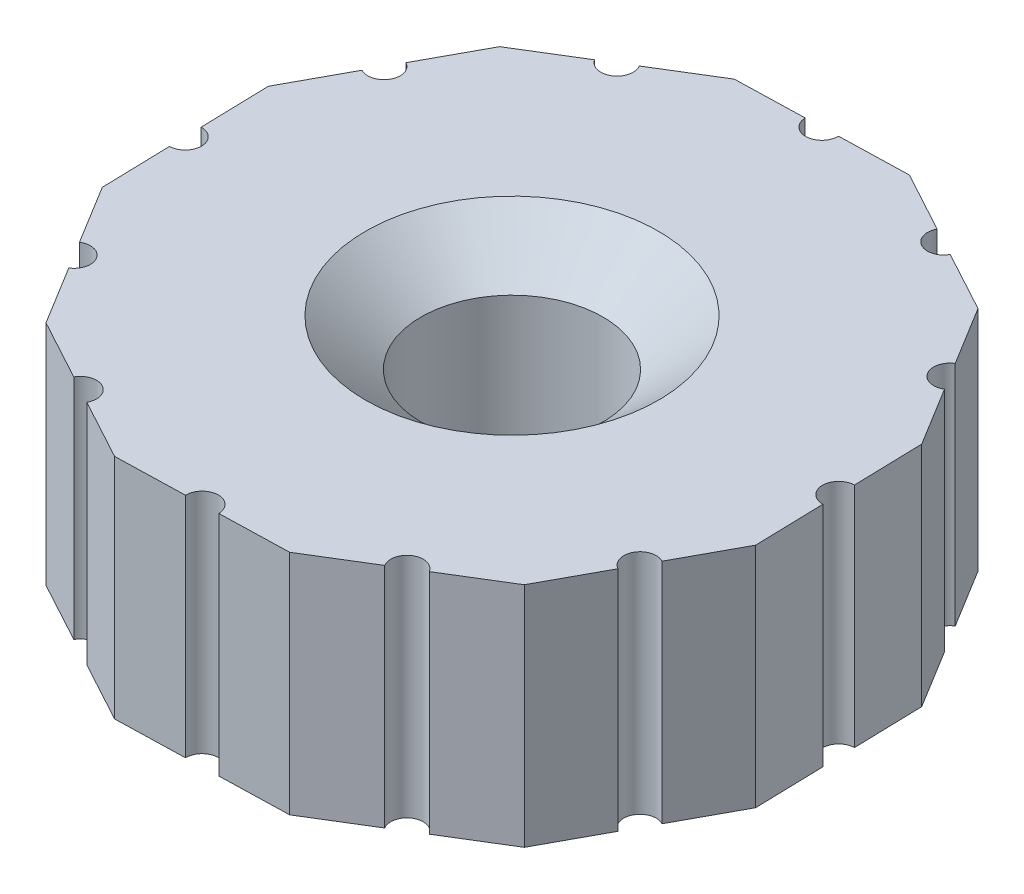
SolidWorks part; units mm, degrees
ref_plane "Front Plane" through (0, 0, 0) normal (0, 0, 1) x (1, 0, 0)
ref_plane "Top Plane" through (0, 0, 0) normal (0, 1, 0) x (1, 0, 0)
ref_plane "Right Plane" through (0, 0, 0) normal (1, 0, 0) x (0, 0, -1)
sketch "Sketch1" plane through (0, 0, 0) normal (0, 1, 0) x (1, 0, 0)
  line L0 (-63.9099, 8.5734) -> (-63.7113, 1.0734)
  line L1 (-35.7211, 1.8147) -> (-35.9197, 9.3146)
  line L2 (-35.9197, 9.3146) -> (-39.8417, 15.7105)
  line L3 (-39.8417, 15.7105) -> (-46.4361, 19.2884)
  line L4 (-46.4361, 19.2884) -> (-53.9361, 19.0898)
  line L5 (-53.9361, 19.0898) -> (-60.3319, 15.1678)
  line L6 (-60.3319, 15.1678) -> (-63.9099, 8.5734)
  line L7 (-63.7113, 1.0734) -> (-59.7893, -5.3224)
  line L8 (-59.7893, -5.3224) -> (-53.1948, -8.9004)
  line L9 (-53.1948, -8.9004) -> (-45.6949, -8.7018)
  line L10 (-45.6949, -8.7018) -> (-39.299, -4.7798)
  line L11 (-39.299, -4.7798) -> (-35.7211, 1.8147)
  circle A1 centre (-49.8155, 5.194) radius 14 construction
  arc A2 (-56.5263, 17.5015) -> (-57.7417, 16.7562) centre (-57.134, 17.1288) cw
  arc A3 (-49.4735, 19.208) -> (-50.8987, 19.1703) centre (-50.1861, 19.1891) cw
  arc A4 (-42.5123, 17.1595) -> (-43.7654, 17.8394) centre (-43.1389, 17.4994) cw
  arc A5 (-37.508, 11.9049) -> (-38.2533, 13.1202) centre (-37.8807, 12.5125) cw
  arc A6 (-35.8015, 4.8521) -> (-35.8392, 6.2772) centre (-35.8204, 5.5646) cw
  arc A7 (-37.85, -2.1091) -> (-37.1701, -0.856) centre (-37.5101, -1.4826) cw
  arc A8 (-43.1046, -7.1134) -> (-41.8893, -6.3681) centre (-42.497, -6.7408) cw
  arc A9 (-50.1574, -8.8199) -> (-48.7323, -8.7822) centre (-49.4449, -8.8011) cw
  arc A10 (-57.1186, -6.7714) -> (-55.8655, -7.4513) centre (-56.4921, -7.1114) cw
  arc A11 (-62.1229, -1.5168) -> (-61.3776, -2.7322) centre (-61.7503, -2.1245) cw
  arc A12 (-63.8294, 5.536) -> (-63.7917, 4.1108) centre (-63.8106, 4.8234) cw
  arc A13 (-61.7809, 12.4972) -> (-62.4608, 11.2441) centre (-62.1209, 11.8706) cw
  circle A14 centre (-49.8155, 5.194) radius 4
  point P53 (-49.8155, 5.194)
  dimension "D1" = 12
extrude "Boss-Extrude1" add sketch "Sketch1" along normal blind 10 contours L6 A13 L0 A12 L7 A11 L8 A10 L9 A9 L10 A8 L11 A7 L1 A6 L2 A5 L3 A4 L4 A3 L5 A2
hole_wizard "CSK for 1/4 Flat Head Machine Screw (100)1" positions "3DSketch2" profile "Sketch15" countersink size "1/4" standard "ANSI Inch" end condition through all
sketch3d "3DSketch2"
  line L0 (-49.8155, 10, -5.194) -> (-49.8155, 0, -5.194) construction
  point P0 (-49.8155, 10, -5.194)
sketch "Sketch15" plane through (-49.8155, 10, -5.194) normal (1, 0, 0) x (0, 0, 1)
  line L0 (0, 0) -> (0, 10)
  line L1 (0, 10) -> (3.5712, 10)
  line L2 (3.5712, 10) -> (3.5712, 2.4063)
  line L3 (3.5712, 2.4063) -> (6.4389, 0)
  line L5 (6.4389, 0) -> (0, 0)
  line L6 (-3.5712, 2.4063) -> (-6.4389, 0) construction
  line L11 (0, -6.35) -> (0, 107.95) construction
  dimension "Thru Hole Dia." = 7.1425
  dimension "Thru Hole Depth" = 10
  dimension "Near C'Sink Dia." = 12.8778
  dimension "Near C'Sink Angle" = 100
